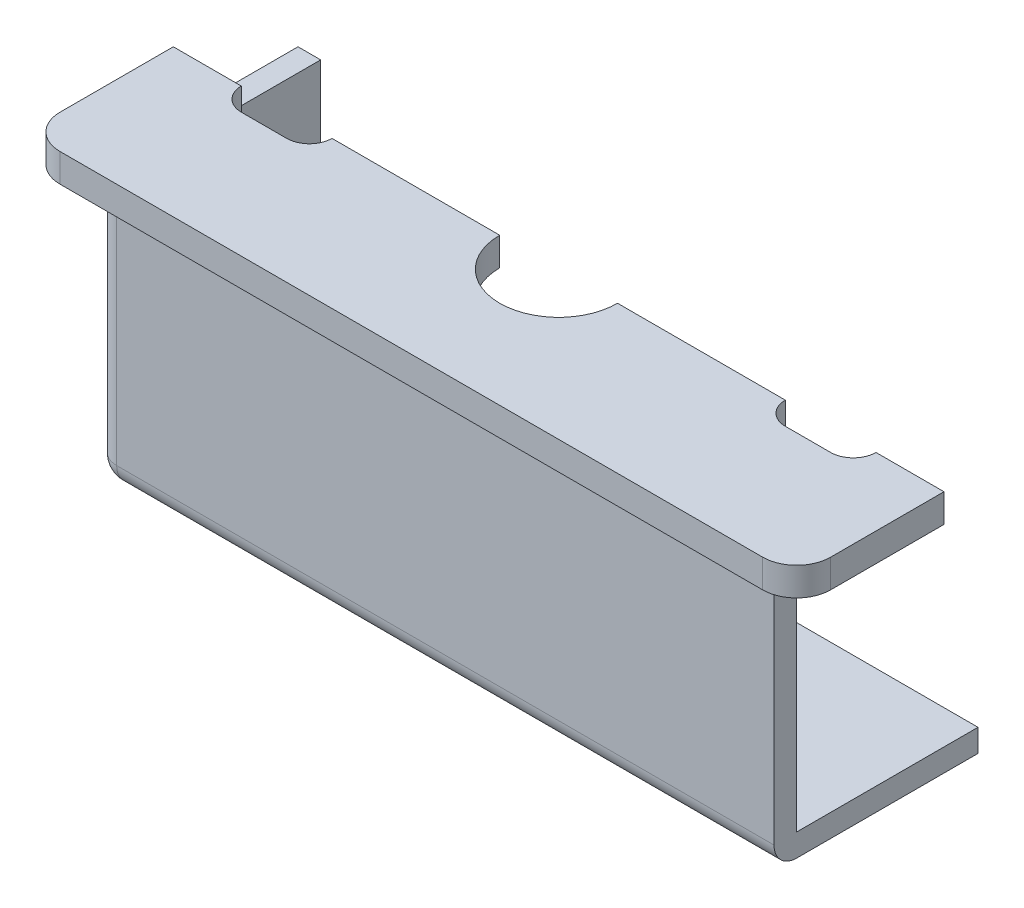
SolidWorks part; units mm, degrees
ref_plane "前视基准面" through (0, 0, 0) normal (0, 0, 1) x (1, 0, 0)
ref_plane "上视基准面" through (0, 0, 0) normal (0, 1, 0) x (1, 0, 0)
ref_plane "右视基准面" through (0, 0, 0) normal (1, 0, 0) x (0, 0, -1)
other "Configuration Table"
sketch "草图1" plane through (0, 0, 0) normal (0, 1, 0) x (1, 0, 0)
  line L1 (-15.5, 4) -> (14.5, 4)
  line L2 (-15.5, 4) -> (-15.5, -5)
  line L3 (-15.5, -5) -> (14.5, -5)
  line L4 (14.5, 4) -> (14.5, -5)
  line L5 (-15.5, 4) -> (14.5, -5) construction
  line L6 (-15.5, -5) -> (14.5, 4) construction
  point P0 (0, 0)
  point P6 (0, 0)
  point P7 (0, 0)
extrude "凸台-拉伸3" add sketch "草图1" against normal blind 12
sketch "草图5" plane through (0, 0, 0) normal (0, 1, 0) x (1, 0, 0)
  line L1 (14.5, 4) -> (-14.5, 4)
  line L2 (14.5, 4) -> (14.5, -4)
  line L3 (14.5, -4) -> (-14.5, -4)
  line L4 (-14.5, 4) -> (-14.5, -4)
extrude "切除-拉伸4" cut sketch "草图5" against normal offset from surface (11 mm away) 1 up to face at (-0.5, -12, 0.5)
sketch "草图6" plane through (0, 0, 0) normal (0, 1, 0) x (1, 0, 0)
  line L0 (-17, 0) -> (-14, 0)
  line L2 (-17, 0) -> (-17, -5)
  line L3 (-15.5, -6.5) -> (15.5, -6.5)
  line L4 (17, 0) -> (17, -5)
  line L8 (2.6, 0) -> (10, 0)
  line L9 (14, 0) -> (17, 0)
  line L11 (-13, -1) -> (-11, -1)
  line L14 (11, -1) -> (13, -1)
  line L16 (-10, 0) -> (-2.6, 0)
  arc A0 (-2.6, 0) -> (2.6, 0) centre (0, 0) ccw
  arc A1 (-14, 0) -> (-13, -1) centre (-13, 0) ccw
  arc A2 (-11, -1) -> (-10, 0) centre (-11, 0) ccw
  arc A3 (10, 0) -> (11, -1) centre (11, 0) ccw
  arc A4 (13, -1) -> (14, 0) centre (13, 0) ccw
  arc A5 (15.5, -6.5) -> (17, -5) centre (15.5, -5) ccw
  arc A6 (-17, -5) -> (-15.5, -6.5) centre (-15.5, -5) ccw
  point P0 (0, 0)
  point P14 (0, 0)
  point P15 (-12, 0)
  point P22 (12, 0)
  dimension "D1" = 1.5
extrude "凸台-拉伸5" add sketch "草图6" along normal blind 1.25
fillet "圆角4" radius 1 3 edges at (-15.5, -6, 5) (-0.5, -12, 5) (-15.5, -12, 0.5)
